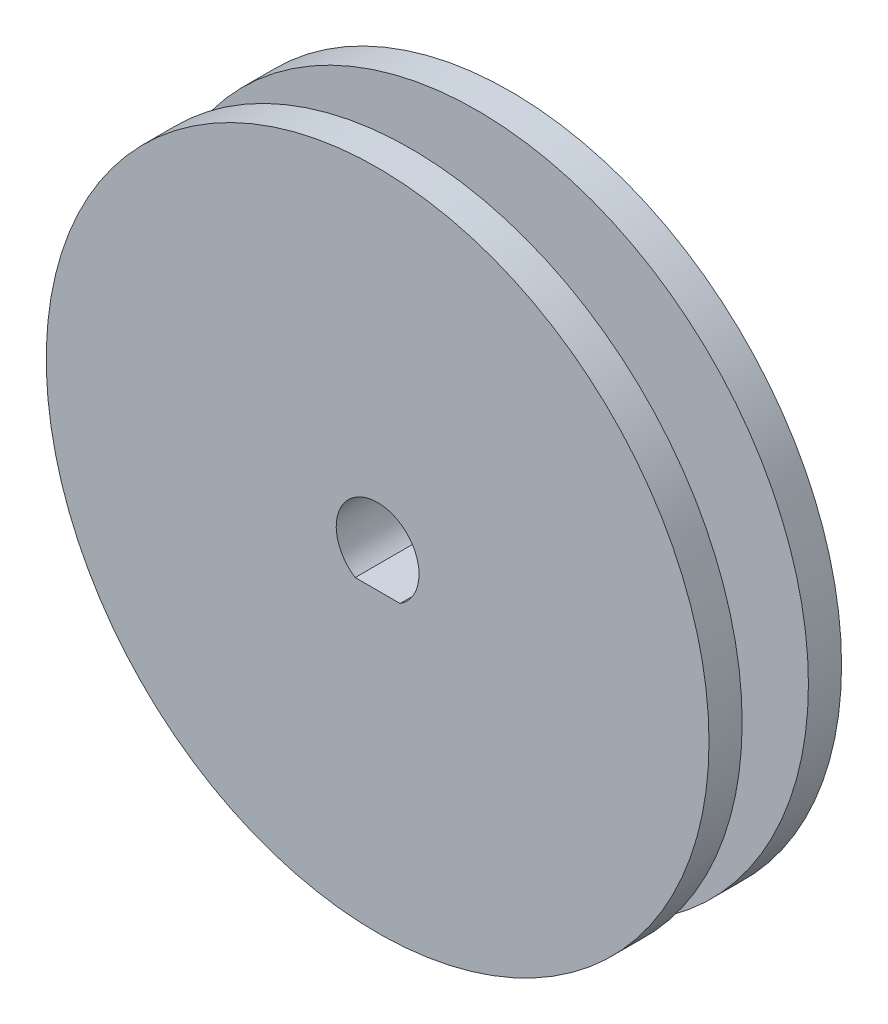
SolidWorks part; units mm, degrees
ref_plane "前视基准面" through (0, 0, 0) normal (0, 0, 1) x (1, 0, 0)
ref_plane "上视基准面" through (0, 0, 0) normal (0, 1, 0) x (1, 0, 0)
ref_plane "右视基准面" through (0, 0, 0) normal (1, 0, 0) x (0, 0, -1)
sketch "草图1" plane through (0, 0, 0) normal (0, 0, 1) x (1, 0, 0)
  circle A0 centre (0, 0) radius 20
  dimension "D1" = 40
extrude "凸台-拉伸1" add sketch "草图1" along normal blind 2
sketch "草图2" plane through (0, 0, 2) normal (0, 0, 1) x (1, 0, 0)
  circle A0 centre (0, 0) radius 10
  dimension "D1" = 20
extrude "凸台-拉伸2" add sketch "草图2" along normal blind 4
ref_plane "基准面4" through (0, 0, 4) normal (0, 0, 1) x (1, 0, 0)
sketch "草图3" plane through (0, 0, 2) normal (0, 0, 1) x (1, 0, 0)
  circle A0 centre (0.0395, 11.6817) radius 1
  dimension "D1" = 2
extrude "凸台-拉伸3" add sketch "草图3" along normal blind 4 contours A0
mirror "镜向2" about plane through (0, 0, 4) normal (0, 0, 1) of "凸台-拉伸1"
sketch "草图4" plane through (0, 0, 8) normal (0, 0, 1) x (1, 0, 0)
  line L0 (-1.3565, -2.1) -> (1.3565, -2.1)
  arc A0 (1.3565, -2.1) -> (-1.3565, -2.1) centre (0, 0) ccw
  point P5 (0, -2.1)
  dimension "D1" = 5
  dimension "D2" = 2.1
extrude "切除-拉伸1" cut sketch "草图4" against normal blind 8 contours A0 L0
